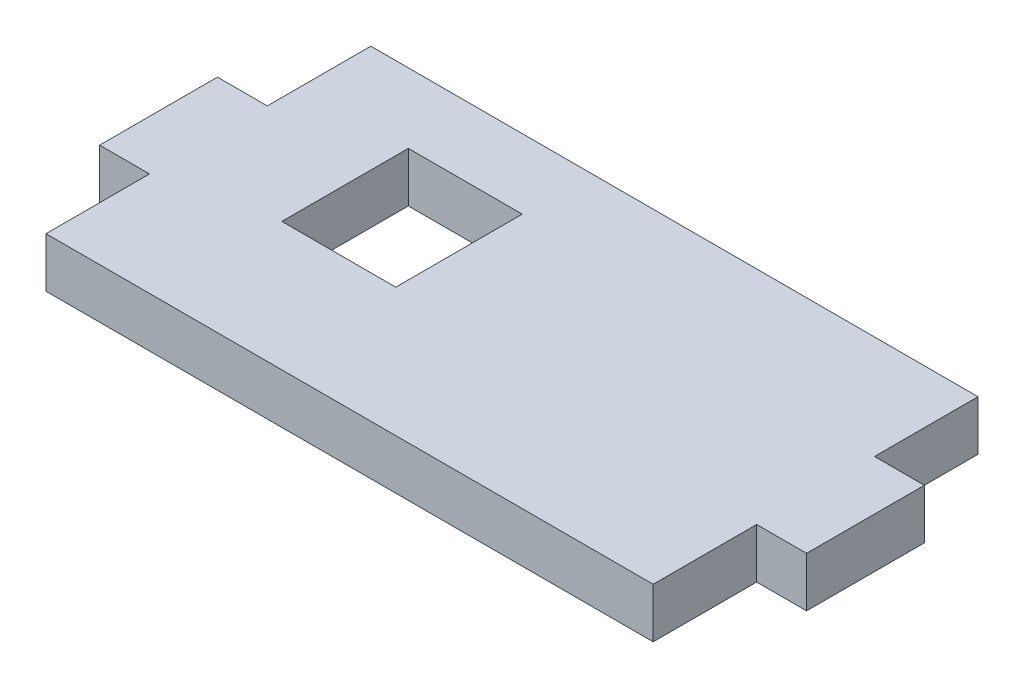
SolidWorks part; units mm, degrees
ref_plane "Front Plane" through (0, 0, 0) normal (0, 0, 1) x (1, 0, 0)
ref_plane "Top Plane" through (0, 0, 0) normal (0, 1, 0) x (1, 0, 0)
ref_plane "Right Plane" through (0, 0, 0) normal (1, 0, 0) x (0, 0, -1)
other "Default"
sketch "Sketch1" plane through (0, 0, 0) normal (0, 1, 0) x (1, 0, 0)
  line L0 (-60.9105, -14.325) -> (170.6381, -14.325) construction
  line L1 (-45, -20.675) -> (45, -20.675)
  line L2 (-45, -20.675) -> (-45, 20.675)
  line L3 (-45, 20.675) -> (45, 20.675)
  line L4 (45, -20.675) -> (45, 20.675)
  line L5 (-45, -20.675) -> (45, 20.675) construction
  line L6 (-45, 20.675) -> (45, -20.675) construction
  point P0 (0, 0)
  dimension "Width" = 90
  dimension "D2" = 6.35
  dimension "D3" = 35
extrude "Boss-Extrude1" add sketch "Sketch1" along normal mid plane 6.35
sketch "Sketch2" plane through (0, 3.175, 0) normal (0, 1, 0) x (1, 0, 0)
  line L0 (-45, -20.675) -> (45, -20.675) construction
  line L1 (-2, -20.675) -> (2, -20.675)
  line L2 (-2, -20.675) -> (-2, -14.325)
  line L3 (-2, -14.325) -> (2, -14.325)
  line L4 (2, -20.675) -> (2, -14.325)
  line L5 (45, -20.675) -> (45, 20.675) construction
  line L6 (45, -7.5) -> (38.65, -7.5)
  line L7 (45, -7.5) -> (45, 7.5)
  line L8 (45, 7.5) -> (38.65, 7.5)
  line L9 (38.65, -7.5) -> (38.65, 7.5)
  line L10 (-45, 20.675) -> (-45, -20.675) construction
  line L11 (-45, 7.5) -> (-38.65, 7.5)
  line L12 (-45, 7.5) -> (-45, -7.5)
  line L13 (-45, -7.5) -> (-38.65, -7.5)
  line L14 (-38.65, 7.5) -> (-38.65, -7.5)
  line L15 (-200060.9105, -14.325) -> (200170.6381, -14.325) construction
  point P18 (-38.65, 0)
  point P20 (0, -14.325)
  dimension "D1" = 43
  dimension "D2" = 15
extrude "FrontBack" [suppressed] cut sketch "Sketch2" against normal through all
sketch "Sketch3" plane through (0, 3.175, 0) normal (0, 1, 0) x (1, 0, 0)
  line L1 (-45, -20.675) -> (-38.65, -20.675)
  line L2 (-45, -20.675) -> (-45, -7.5)
  line L3 (-45, -7.5) -> (-38.65, -7.5)
  line L4 (-38.65, -20.675) -> (-38.65, -7.5)
  line L5 (-45, 20.675) -> (-38.65, 20.675)
  line L6 (-45, 20.675) -> (-45, 7.5)
  line L7 (-45, 7.5) -> (-38.65, 7.5)
  line L8 (-38.65, 20.675) -> (-38.65, 7.5)
  line L9 (45, 20.675) -> (38.65, 20.675)
  line L10 (45, 20.675) -> (45, 7.5)
  line L11 (45, 7.5) -> (38.65, 7.5)
  line L12 (38.65, 20.675) -> (38.65, 7.5)
  line L13 (45, -20.675) -> (38.65, -20.675)
  line L14 (45, -20.675) -> (45, -7.5)
  line L15 (45, -7.5) -> (38.65, -7.5)
  line L16 (38.65, -20.675) -> (38.65, -7.5)
extrude "LeftRight" cut sketch "Sketch3" against normal through all
sketch "Sketch4" plane through (0, -3.175, 0) normal (0, -1, 0) x (1, 0, 0)
  line L0 (-23.8955, 0.6961) -> (-11.5845, 0.6961) construction
  line L1 (-10.49, 4.3076) -> (-24.99, 4.3076)
  line L2 (-10.49, 4.3076) -> (-10.49, -11.7924)
  line L3 (-10.49, -11.7924) -> (-24.99, -11.7924)
  line L4 (-24.99, 4.3076) -> (-24.99, -11.7924)
  line L5 (-23.8955, 0.6961) -> (-11.5845, 0.6961) construction
  line L6 (-11.5845, 0.6961) -> (-11.5845, -8.181) construction
  line L7 (-11.5845, 0.6961) -> (-11.5845, -8.181) construction
  point P6 (-17.74, 0.6961)
  point P8 (-17.74, 4.3076)
  point P9 (-11.5845, -3.7424)
  point P10 (-10.49, -3.7424)
  dimension "D1" = 14.5
  dimension "D2" = 16.1
extrude "Right" cut sketch "Sketch4" against normal through all
